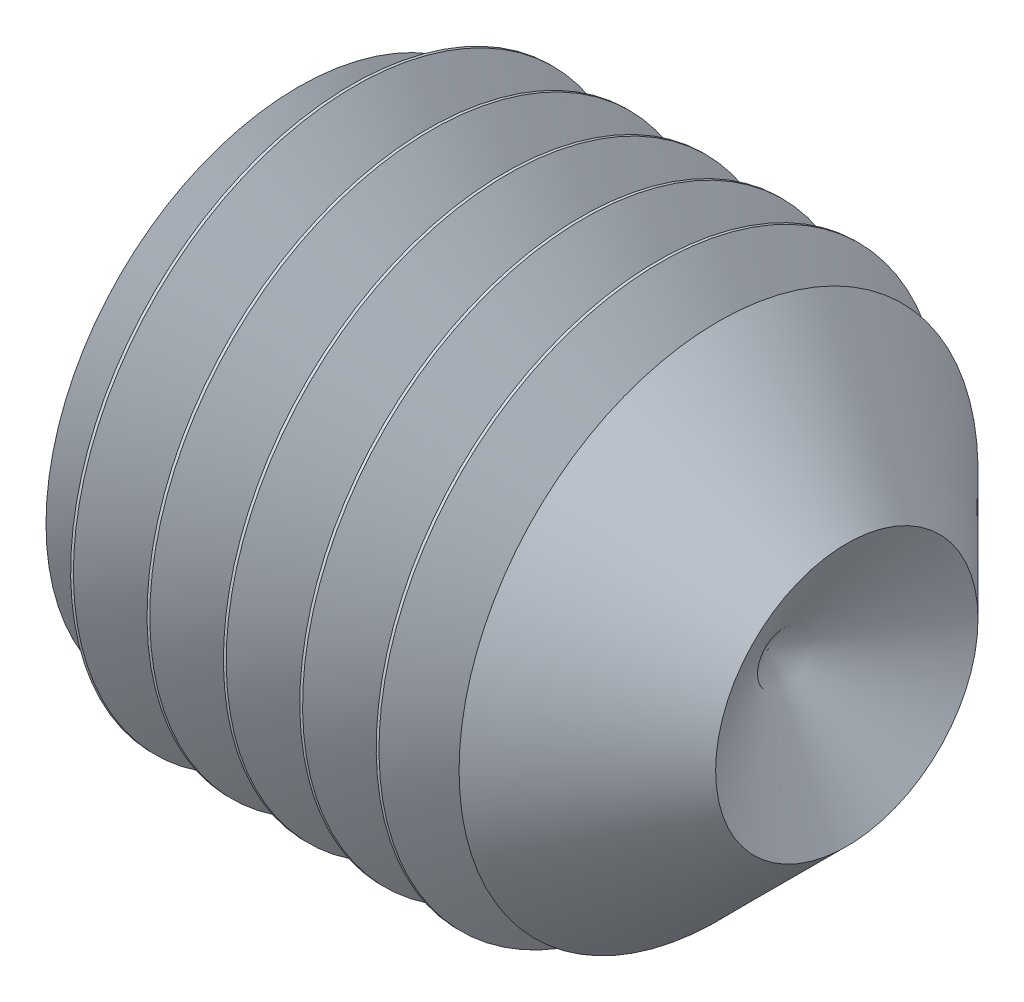
SolidWorks part; units mm, degrees
revolve "BaseBody" add sketch "BodySke" angle 360 about L5
sketch "BodySke" plane through (0, 0, 0) normal (0, 0, 1) x (1, 0, 0)
  line L0 (0, 0) -> (0, 1.2195)
  line L1 (0, 1.2195) -> (0.1619, 1.5)
  line L2 (0.1619, 1.5) -> (2.2, 1.5)
  line L3 (2.2, 1.5) -> (3, 0.7)
  line L4 (2.5794, 0) -> (0, 0)
  line L5 (-12.7, 0) -> (88.9, 0) construction
  line L6 (2.5794, 0) -> (3, 0.7)
  line L7 (3, 0.7) -> (3, 10.225) construction
  line L8 (0, -1.2195) -> (0.1619, -1.5) construction
  line L9 (2.5794, 0) -> (3, -0.7) construction
  line L10 (2.2, -1.5) -> (3, -0.7) construction
  line L11 (0.5, 15.875) -> (0.5, -3.175) construction
  dimension "Diameter" = 3
  dimension "Drive_ch_ang" = 60
  dimension "Minor_dia" = 2.439
  dimension "Cup_nose_ang" = 45
  dimension "Cup_ang" = 118
  dimension "Cup_dia" = 1.4
  dimension "Length" = 3
  dimension "Advance" = 0.5
cosmetic thread "ThreadCosmetic" [suppressed] parameters "Thread_minor"=2.439
ref_plane "Plane1" through (0, 0, 0) normal (0, 0, 1) x (1, 0, 0)
ref_plane "Plane2" through (0, 0, 0) normal (0, 1, 0) x (1, 0, 0)
ref_plane "Plane3" through (0, 0, 0) normal (1, 0, 0) x (0, 0, -1)
sketch "Sketch2" plane through (0, 0, 0) normal (-1, 0, 0) x (0, 0, 1)
  line L0 (0.433, 0.75) -> (-0.433, 0.75)
  line L1 (-0.433, 0.75) -> (-0.866, 0)
  line L2 (0.433, 0.75) -> (0.866, 0)
  line L3 (0.433, -0.75) -> (0.866, 0)
  line L4 (0.433, -0.75) -> (-0.433, -0.75)
  line L5 (-0.433, -0.75) -> (-0.866, 0)
  dimension "Hex_size" = 1.5
  dimension "D2" = 0.75
  dimension "D3" = 0.75
extrude "Hex" cut sketch "Sketch2" against normal blind 1.5
sketch "Sketch4" plane through (0, 4.7709, -0.5249) normal (-1, 0, 0) x (0, 0, 1)
  line L0 (0.5249, -4.7709) -> (1.3124, -4.7709)
  line L1 (0.5249, -4.7709) -> (6.6732, -1.2211) construction
  line L2 (0.5249, -4.7709) -> (0.9186, -4.0889)
  line L3 (1.153, -4.6137) -> (1.2782, -4.5415)
  line L4 (0.975, -4.3054) -> (1.1002, -4.2332)
  arc A0 (1.153, -4.6137) -> (0.975, -4.3054) centre (0.5249, -4.7709) ccw
  arc A1 (1.3124, -4.7709) -> (1.2782, -4.5415) centre (0.5249, -4.7709) ccw
  arc A2 (0.9186, -4.0889) -> (1.1002, -4.2332) centre (0.5249, -4.7709) cw
  circle A3 centre (0.5249, -4.7709) radius 0.6475 construction
  circle A4 centre (0.5249, -4.7709) radius 0.7875 construction
  dimension "Spline_n_dim" = 1.295
  dimension "Spline_m_dim" = 1.575
  dimension "D1" = 30
  dimension "Spline_a_dim" = 60
  dimension "Spline_p_dim" = 0.356
  dimension "D3" = 0.178
extrude "Spline6" [suppressed] cut sketch "Sketch4" against normal blind 1.2
pattern_circular "CirPattern1" [suppressed] count 6 every 60 about axis through (-12.7, 0, 0) along (1, 0, 0)
sketch "Sketch5" plane through (0, 1.5227, 6.1981) normal (-1, 0, 0) x (0, 0, 1)
  line L0 (-6.1981, -1.5227) -> (-5.4106, -1.5227)
  line L1 (-6.1981, -1.5227) -> (-1.178, 3.4975) construction
  line L2 (-6.1981, -1.5227) -> (-6.1981, -0.7352)
  line L3 (-5.6144, -1.1907) -> (-5.5298, -1.1061)
  line L4 (-5.8661, -0.9389) -> (-5.7815, -0.8544)
  line L5 (-5.8661, -0.9389) -> (-5.6144, -1.1907)
  arc A1 (-5.4106, -1.5227) -> (-5.5298, -1.1061) centre (-6.1981, -1.5227) ccw
  arc A2 (-6.1981, -0.7352) -> (-5.7815, -0.8544) centre (-6.1981, -1.5227) cw
  circle A3 centre (-6.1981, -1.5227) radius 0.6475 construction
  circle A4 centre (-6.1981, -1.5227) radius 0.7875 construction
  dimension "Spline_n_dim" = 1.295
  dimension "Spline_m_dim" = 1.575
  dimension "Spline_p_dim" = 0.356
  dimension "D3" = 0.178
  dimension "D1" = 45
  dimension "Spline_a_dim" = 90
extrude "Spline4" [suppressed] cut sketch "Sketch5" against normal blind 1.2
pattern_circular "CirPattern2" [suppressed] count 4 every 90 about axis through (-12.7, 0, 0) along (1, 0, 0)
sketch "ThdSchSke" plane through (0, 0, 0) normal (0, 0, 1) x (1, 0, 0)
  line L0 (0.1619, -1.2195) -> (-0.0345, -1.5)
  line L1 (0.1619, -1.2195) -> (0.3584, -1.5)
  line L2 (0.3584, -1.5) -> (0.3584, -1.875)
  line L3 (-3.175, 0) -> (5.1513, 0) construction
  line L4 (0.1619, 1.5) -> (0.1619, -1.5) construction
  line L5 (0.3584, -1.875) -> (-0.0345, -1.875)
  line L6 (-0.0345, -1.875) -> (-0.0345, -1.5)
  dimension "Thread_minor" = 2.439
  dimension "Diameter" = 3
revolve "ThreadSchematic" cut sketch "ThdSchSke" angle 360 about L3
pattern_linear "ThdSchPat" count 6 spacing 0.4076 along (1, 0, 0) of "ThreadSchematic"
equation "\"D2@Sketch2\" = \"Hex_size@Sketch2\" / 2"
equation "\"D3@Sketch2\" = \"Hex_size@Sketch2\" / 2"
equation "\"Thread_minor@ThreadCosmetic\" = \"Minor_dia@BodySke\""
equation "\"D1@Sketch4\" = \"Spline_a_dim@Sketch4\" / 2"
equation "\"D3@Sketch4\" = \"Spline_p_dim@Sketch4\" / 2"
equation "\"D2@CirPattern1\" = \"Spline_a_dim@Sketch4\""
equation "\"Num_teeth@CirPattern1\" = 360 / \"D2@CirPattern1\""
equation "\"Spline_a_dim@Sketch5\" = 90"
equation "\"Spline_p_dim@Sketch5\" = \"Spline_p_dim@Sketch4\""
equation "\"Spline_m_dim@Sketch5\" = \"Spline_m_dim@Sketch4\""
equation "\"Spline_n_dim@Sketch5\" = \"Spline_n_dim@Sketch4\""
equation "\"D1@Sketch5\" = \"Spline_a_dim@Sketch5\" / 2"
equation "\"D3@Sketch5\" = \"Spline_p_dim@Sketch5\" / 2"
equation "\"Key_eng@Spline4\" = \"Key_eng@Spline6\""
equation "\"Thread_minor@ThdSchSke\" = \"Thread_minor@ThreadCosmetic\""
equation "\"Diameter@ThdSchSke\" = \"Diameter@BodySke\""
equation "\"Overcut@ThdSchSke\" = \"Diameter@BodySke\" * 1.25"
equation "\"Num_threads@ThdSchPat\" = int( (\"Length@BodySke\" - ( ( ( \"Diameter@BodySke\" - \"Minor_dia@BodySke\" ) * 0.5 ) / tan( \"Drive_ch_ang@BodySke\" * 0.017453292 ) ) - ( ( ( \"Diameter@BodySke\" - \"Cup_dia@BodySke\" ) * 0.5 ) * tan( \"Cup_nose_ang@BodySke\" * 0.017453292 ) ) ) / \"Advance@BodySke\" + 0.999 )  + 1"
equation "\"Advance@ThdSchPat\" = (\"Length@BodySke\" - ( ( ( \"Diameter@BodySke\" - \"Minor_dia@BodySke\" ) * 0.5 ) / tan( \"Drive_ch_ang@BodySke\" * 0.017453292 ) ) - ( ( ( \"Diameter@BodySke\" - \"Cup_dia@BodySke\" ) * 0.5 ) * tan( \"Cup_nose_ang@BodySke\" * 0.017453292 ) ) ) /  (\"Num_threads@ThdSchPat\" - 1) 'relax it"
equation "' \"Num_threads@ThdSchPat\" = \"Num_threads@ThdSchPat\" - sgn( \"Num_threads@ThdSchPat\" - 1) '---chamfered tips only---"
